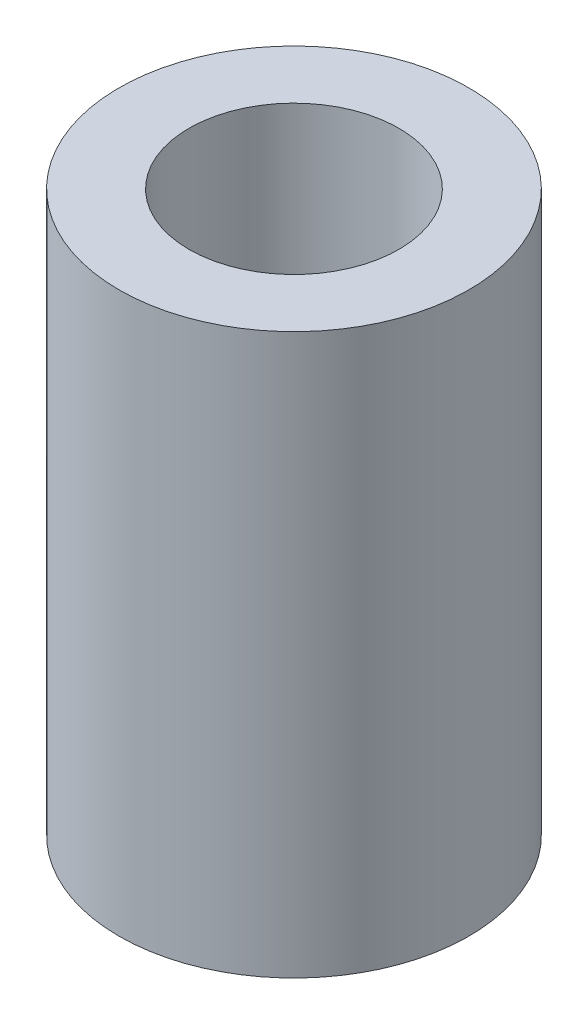
SolidWorks part; units mm, degrees
material "黄铜"
ref_plane "前视基准面" through (0, 0, 0) normal (0, 0, 1) x (1, 0, 0)
ref_plane "上视基准面" through (0, 0, 0) normal (0, 1, 0) x (1, 0, 0)
ref_plane "右视基准面" through (0, 0, 0) normal (1, 0, 0) x (0, 0, -1)
other "Configuration Table"
sketch "草图1" plane through (0, 0, 0) normal (0, 1, 0) x (1, 0, 0)
  circle A0 centre (0, 0) radius 2.5
  circle A1 centre (0, 0) radius 1.5
  dimension "D1" = 5
  dimension "D2" = 3
extrude "凸台-拉伸1" add sketch "草图1" along normal mid plane 8
